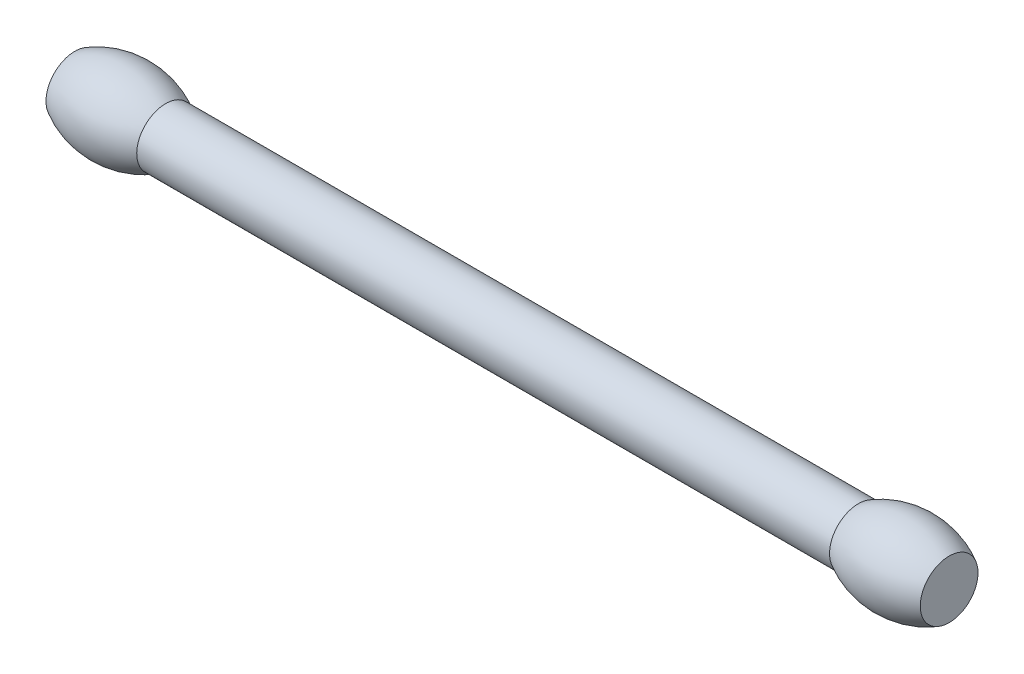
SolidWorks part; units mm, degrees
material "Chrome Stainless Steel"
ref_plane "Front Plane" through (0, 0, 0) normal (0, 0, 1) x (1, 0, 0)
ref_plane "Top Plane" through (0, 0, 0) normal (0, 1, 0) x (1, 0, 0)
ref_plane "Right Plane" through (0, 0, 0) normal (1, 0, 0) x (0, 0, -1)
sketch "Sketch1" plane through (0, 0, 0) normal (0, 0, 1) x (1, 0, 0)
  line L0 (-48.006, 0) -> (-54.2925, 0) construction
  line L1 (66.409, 0) -> (86.8277, 0) construction
  line L3 (48.006, 4.0005) -> (-48.006, 4.0005)
  line L4 (60.579, 5.6515) -> (54.2925, 0) construction
  line L5 (0, 0) -> (-48.006, 4.0005) construction
  line L6 (48.006, 4.0005) -> (0, 0) construction
  line L7 (54.2925, 0) -> (48.006, 5.6515) construction
  line L8 (-60.579, 0) -> (48.006, 0)
  line L9 (48.006, 0) -> (54.2925, 0) construction
  line L10 (-60.579, 0) -> (-60.579, 5.6515)
  line L11 (-60.579, 5.6515) -> (-48.006, 5.6515)
  line L12 (60.579, 5.6515) -> (48.006, 5.6515)
  line L13 (-54.2925, 0) -> (-48.006, 5.6515) construction
  line L14 (-60.579, 5.6515) -> (-54.2925, 0) construction
  line L15 (60.579, 0) -> (60.579, 5.6515)
  line L16 (48.006, 0) -> (60.579, 0)
  line L17 (48.006, 4.0005) -> (48.006, 5.6515)
  arc A0 (-48.006, 4.0005) -> (-60.579, 4.0005) centre (-54.2925, -7.1425) ccw
  arc A1 (48.006, 4.0005) -> (60.579, 4.0005) centre (54.2925, -7.1425) cw
  point P0 (0, 0)
  dimension "D3" = 6.2865
revolve "Revolve1" add sketch "Sketch1" angle 360 about L1
